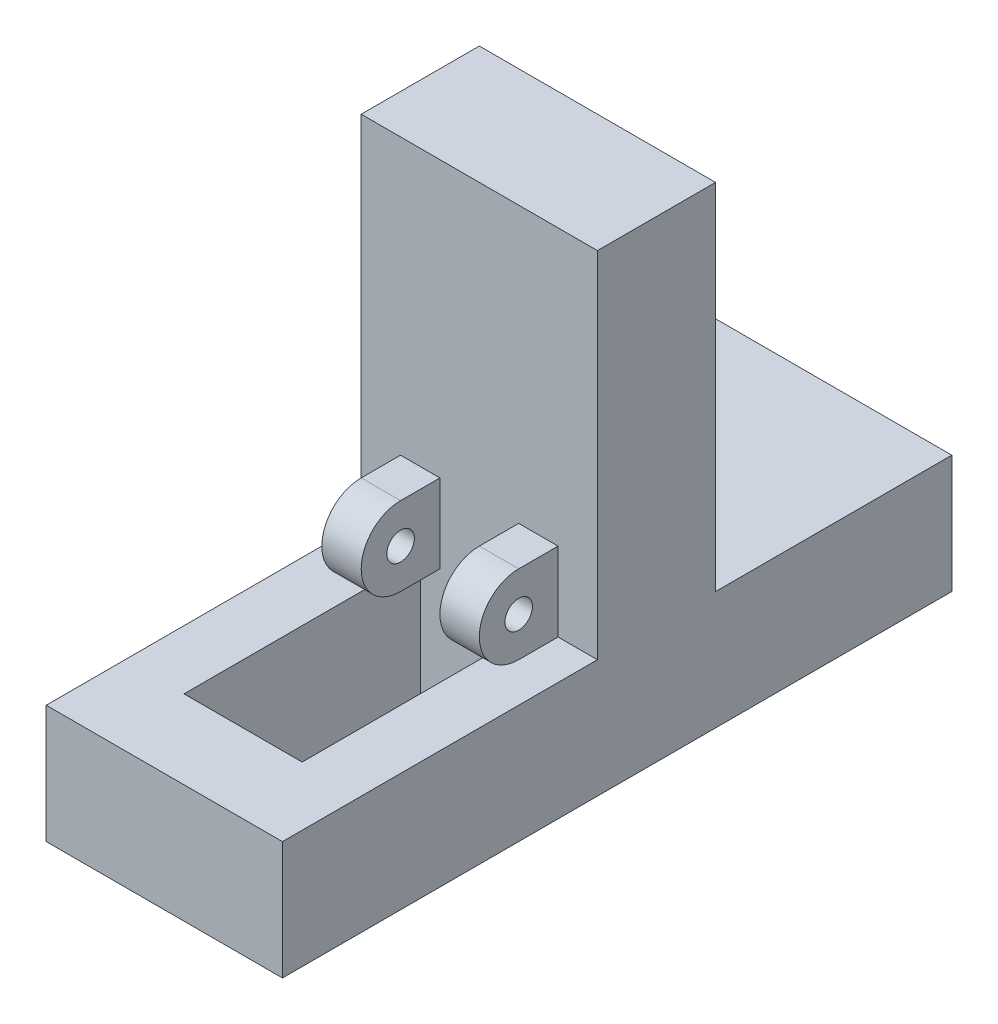
SolidWorks part; units mm, degrees
ref_plane "Front Plane" through (0, 0, 0) normal (0, 0, 1) x (1, 0, 0)
ref_plane "Top Plane" through (0, 0, 0) normal (0, 1, 0) x (1, 0, 0)
ref_plane "Right Plane" through (0, 0, 0) normal (1, 0, 0) x (0, 0, -1)
sketch "Sketch1" plane through (0, 0, 0) normal (0, 0, 1) x (1, 0, 0)
  line L1 (0, 0) -> (30, 0)
  line L2 (0, 0) -> (0, 60)
  line L3 (0, 60) -> (30, 60)
  line L4 (30, 0) -> (30, 60)
  circle A0 centre (15, 10) radius 1.75
  point P7 (15, 0)
  dimension "D4" = 3.5
  dimension "D1" = 30
  dimension "D2" = 60
  dimension "D3" = 10
extrude "Boss-Extrude1" add sketch "Sketch1" along normal blind 15
sketch "Sketch4" plane through (30, 0, 0) normal (1, 0, 0) x (0, 0, -1)
  line L0 (-15, 15) -> (-20, 15)
  line L1 (-15, 0) -> (-15, 60) construction
  line L2 (-15, 15) -> (-15, 25)
  line L3 (-15, 25) -> (-20, 25)
  line L5 (-15, 0) -> (0, 0) construction
  arc A0 (-20, 25) -> (-20, 15) centre (-20, 20) ccw
  circle A1 centre (-20, 20) radius 1.75
  dimension "D1" = 3.5
  dimension "D2" = 10
  dimension "D3" = 5
  dimension "D4" = 20
extrude "Boss-Extrude3" add sketch "Sketch4" against normal up to surface (30 mm away) up to face at (0, 30, 7.5)
sketch "Sketch5" plane through (0, 0, 15) normal (0, 0, 1) x (1, 0, 0)
  line L0 (0, 15) -> (30, 15) construction
  line L1 (0, 25) -> (5, 25)
  line L2 (0, 25) -> (0, 15)
  line L3 (0, 15) -> (5, 15)
  line L4 (5, 25) -> (5, 15)
  line L5 (0, 25) -> (30, 25) construction
  line L6 (10, 15) -> (20, 15)
  line L7 (10, 15) -> (10, 25)
  line L8 (10, 25) -> (20, 25)
  line L9 (20, 15) -> (20, 25)
  line L10 (0, 60) -> (0, 25) construction
  line L11 (30, 25) -> (25, 25)
  line L12 (30, 25) -> (30, 15)
  line L13 (30, 15) -> (25, 15)
  line L14 (25, 25) -> (25, 15)
  dimension "D1" = 5
  dimension "D2" = 5
  dimension "D3" = 10
  dimension "D4" = 5
extrude "Cut-Extrude1" cut sketch "Sketch5" along normal through all
sketch "Sketch6" plane through (0, 0, 15) normal (0, 0, 1) x (1, 0, 0)
  line L0 (5, 15) -> (10, 15) construction
  line L1 (0, 0) -> (7.5, 0)
  line L2 (0, 0) -> (0, 15)
  line L3 (0, 15) -> (7.5, 15)
  line L4 (7.5, 0) -> (7.5, 15)
  line L5 (20, 15) -> (25, 15) construction
  line L6 (30, 0) -> (22.5, 0)
  line L7 (30, 0) -> (30, 15)
  line L8 (30, 15) -> (22.5, 15)
  line L9 (22.5, 0) -> (22.5, 15)
extrude "Boss-Extrude4" add sketch "Sketch6" along normal blind 30
sketch "Sketch7" plane through (0, 0, 45) normal (0, 0, 1) x (1, 0, 0)
  line L1 (0, 15) -> (30, 15)
  line L2 (0, 15) -> (0, 0)
  line L3 (0, 0) -> (30, 0)
  line L4 (30, 15) -> (30, 0)
extrude "Boss-Extrude5" add sketch "Sketch7" along normal blind 10
sketch "Sketch8" plane through (0, 0, 0) normal (0, 0, -1) x (-1, 0, 0)
  line L0 (0, 60) -> (0, 0) construction
  line L1 (-30, 0) -> (0, 0)
  line L2 (-30, 0) -> (-30, 15)
  line L3 (-30, 15) -> (0, 15)
  line L4 (0, 0) -> (0, 15)
  circle A0 centre (-15, 10) radius 1.75
  dimension "D1" = 15
extrude "Boss-Extrude6" add sketch "Sketch8" along normal blind 30
